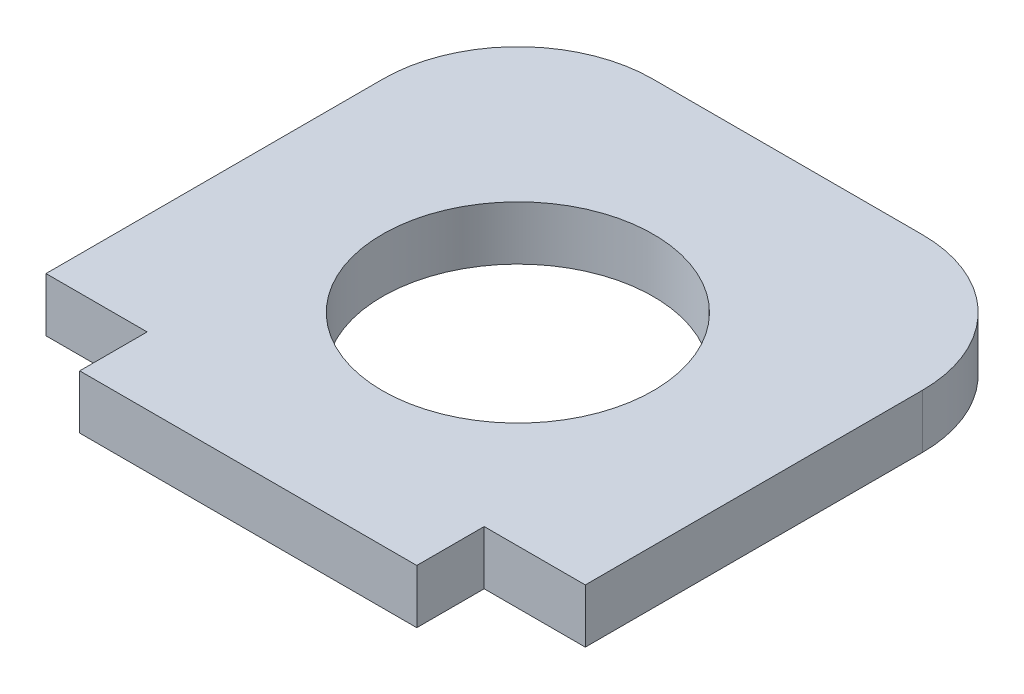
SolidWorks part; units mm, degrees
material "AISI 4340 Сталь, отожженная"
ref_plane "Спереди" through (0, 0, 0) normal (0, 0, 1) x (1, 0, 0)
ref_plane "Сверху" through (0, 0, 0) normal (0, 1, 0) x (1, 0, 0)
ref_plane "Справа" through (0, 0, 0) normal (1, 0, 0) x (0, 0, -1)
sketch "Эскиз1" plane through (0, 0, 0) normal (0, 1, 0) x (1, 0, 0)
  line L1 (-20, -15) -> (-12.5, -15)
  line L2 (-12.5, -15) -> (-12.5, -20)
  line L3 (-12.5, -20) -> (12.5, -20)
  line L4 (12.5, -15) -> (12.5, -20)
  line L5 (0, 12.5) -> (0, -49987.5) construction
  line L6 (-20, -15) -> (-20, 20)
  line L9 (20, 20) -> (-20, 20)
  line L11 (20, -15) -> (20, 20)
  line L13 (12.5, -15) -> (20, -15)
  point P0 (0, 0)
  dimension "D5" = 40
  dimension "D3" = 20
  dimension "D1" = 25
  dimension "D2" = 5
  dimension "D4" = 40
extrude "Бобышка-Вытянуть1" add sketch "Эскиз1" along normal blind 4
sketch "Эскиз5" plane through (0, 4, 0) normal (0, 1, 0) x (1, 0, 0)
  circle A0 centre (0, 0) radius 10.05
  dimension "D1" = 20.1
extrude "Вырез-Вытянуть4" cut sketch "Эскиз5" against normal through all
fillet "Скругление1" radius 10 2 edges at (20, 2, -20) (-20, 2, -20)
